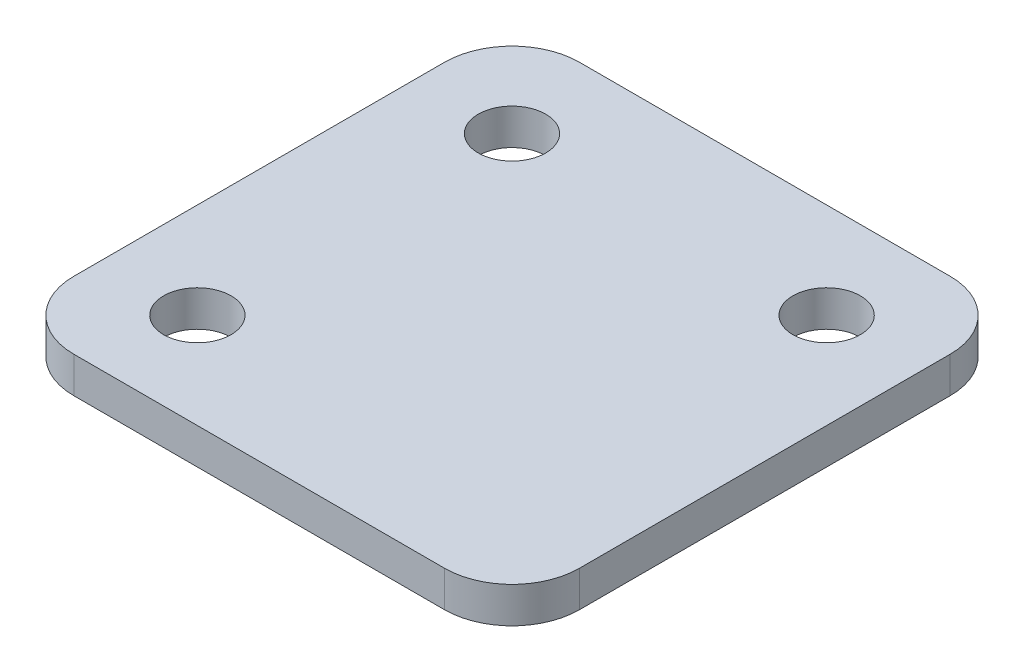
SolidWorks part; units mm, degrees
ref_plane "Front Plane" through (0, 0, 0) normal (0, 0, 1) x (1, 0, 0)
ref_plane "Top Plane" through (0, 0, 0) normal (0, 1, 0) x (1, 0, 0)
ref_plane "Right Plane" through (0, 0, 0) normal (1, 0, 0) x (0, 0, -1)
sketch "Sketch1" plane through (0, 0, 0) normal (0, 1, 0) x (1, 0, 0)
  line L0 (0, 11.25) -> (0, -11.25) construction
  line L1 (8.25, 11.25) -> (-8.25, 11.25)
  line L2 (11.25, 8.25) -> (11.25, -8.25)
  line L3 (8.25, -11.25) -> (-8.25, -11.25)
  line L4 (-11.25, 8.25) -> (-11.25, -8.25)
  line L5 (11.25, 11.25) -> (-11.25, -11.25) construction
  line L6 (11.25, -11.25) -> (-11.25, 11.25) construction
  line L7 (-11.25, 0) -> (11.25, 0) construction
  circle A0 centre (7, 7) radius 1.5
  circle A1 centre (-7, 7) radius 1.5
  circle A2 centre (-7, -7) radius 1.5
  arc A3 (-8.25, -11.25) -> (-11.25, -8.25) centre (-8.25, -8.25) cw
  arc A4 (11.25, -8.25) -> (8.25, -11.25) centre (8.25, -8.25) cw
  arc A5 (8.25, 11.25) -> (11.25, 8.25) centre (8.25, 8.25) cw
  arc A6 (-8.25, 11.25) -> (-11.25, 8.25) centre (-8.25, 8.25) ccw
  point P0 (0, 0)
  dimension "D4" = 3
  dimension "D5" = 3
  dimension "D1" = 22.5
  dimension "D2" = 14
  dimension "D3" = 14
extrude "Boss-Extrude1" add sketch "Sketch1" along normal blind 1.6
sketch "Sketch2" plane through (0, 0, 0) normal (0, -1, 0) x (1, 0, 0)
  line L1 (-2.15, 2.6) -> (2.15, 2.6)
  line L2 (-2.15, 2.6) -> (-2.15, -2.6)
  line L3 (-2.15, -2.6) -> (2.15, -2.6)
  line L4 (2.15, 2.6) -> (2.15, -2.6)
  line L5 (-2.15, 2.6) -> (2.15, -2.6) construction
  line L6 (-2.15, -2.6) -> (2.15, 2.6) construction
  point P0 (0, 0)
  dimension "D1" = 5.2
  dimension "D2" = 4.3
extrude "Boss-Extrude2" add sketch "Sketch2" along normal blind 1
